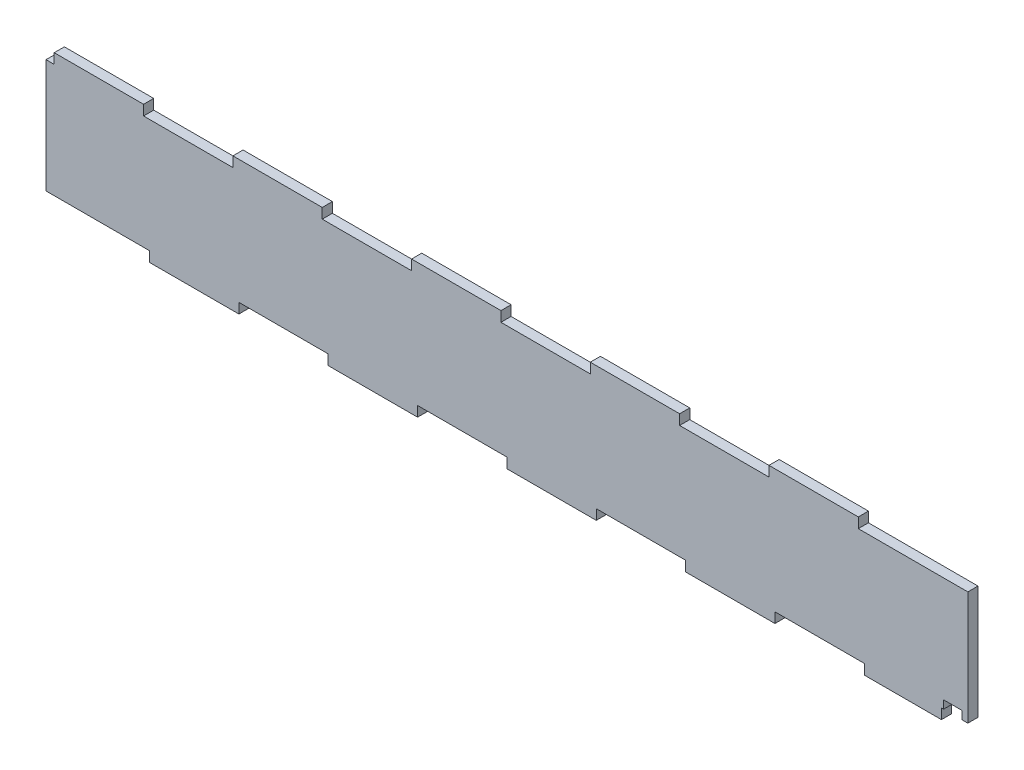
SolidWorks part; units mm, degrees
ref_plane "Front Plane" through (0, 0, 0) normal (0, 0, 1) x (1, 0, 0)
ref_plane "Top Plane" through (0, 0, 0) normal (0, 1, 0) x (1, 0, 0)
ref_plane "Right Plane" through (0, 0, 0) normal (1, 0, 0) x (0, 0, -1)
sketch "Sketch1" plane through (0, 0, 0) normal (0, 0, 1) x (1, 0, 0)
  line L0 (305.05, 56) -> (349.05, 56)
  line L1 (41.05, 56) -> (85.05, 56)
  line L2 (435.06, 4) -> (444.06, 4)
  line L3 (396, 0) -> (352, 0)
  line L5 (-2.95, 61) -> (41.05, 61)
  line L7 (129.05, 56) -> (173.05, 56)
  line L9 (85.05, 61) -> (129.05, 61)
  line L10 (41.05, 56) -> (41.05, 61)
  line L11 (217.05, 56) -> (261.05, 56)
  line L12 (129.05, 56) -> (129.05, 61)
  line L13 (173.05, 61) -> (217.05, 61)
  line L17 (261.05, 61) -> (305.05, 61)
  line L18 (217.05, 56) -> (217.05, 61)
  line L19 (393.05, 56) -> (447, 56)
  line L20 (393.05, 56) -> (393.05, 61)
  line L21 (349.05, 61) -> (393.05, 61)
  line L23 (308, 0) -> (264, 0)
  line L24 (435.06, 4) -> (435.06, 0)
  line L25 (434, -5) -> (396, -5)
  line L26 (396, -5) -> (396, 0)
  line L27 (220, 0) -> (176, 0)
  line L28 (352, 0) -> (352, -5)
  line L29 (352, -5) -> (308, -5)
  line L30 (308, -5) -> (308, 0)
  line L31 (132, 0) -> (88, 0)
  line L32 (264, 0) -> (264, -5)
  line L33 (264, -5) -> (220, -5)
  line L34 (220, -5) -> (220, 0)
  line L35 (44, 0) -> (0, 0)
  line L36 (176, 0) -> (176, -5)
  line L37 (176, -5) -> (132, -5)
  line L38 (132, -5) -> (132, 0)
  line L40 (88, 0) -> (88, -5)
  line L41 (88, -5) -> (44, -5)
  line L42 (44, -5) -> (44, 0)
  line L43 (447, 56) -> (447, 0)
  line L44 (447, 0) -> (444.06, 0)
  line L45 (0, 0) -> (-7, 0)
  line L46 (-7, 0) -> (-7, 56)
  line L47 (-7, 56) -> (-2.95, 56)
  line L48 (434, 0) -> (434, -5)
  line L49 (435.06, 0) -> (434, 0)
  line L50 (444.06, 4) -> (444.06, 0)
  line L51 (305.05, 56) -> (305.05, 61)
  line L53 (349.05, 61) -> (349.05, 56)
  line L55 (261.05, 61) -> (261.05, 56)
  line L57 (173.05, 61) -> (173.05, 56)
  line L59 (85.05, 61) -> (85.05, 56)
  line L60 (-2.95, 61) -> (-2.95, 56)
  dimension "D1" = 454
  dimension "D2" = 56
  dimension "D3" = 44
  dimension "D4" = 44
  dimension "D5" = 1.06
  dimension "D6" = 4
  dimension "D7" = 38
  dimension "D8" = 9
  dimension "D9" = 44
  dimension "D10" = 44
  dimension "D11" = 44
  dimension "D12" = 44
  dimension "D13" = 44
  dimension "D14" = 44
extrude "Boss-Extrude1" add sketch "Sketch1" along normal blind 5
